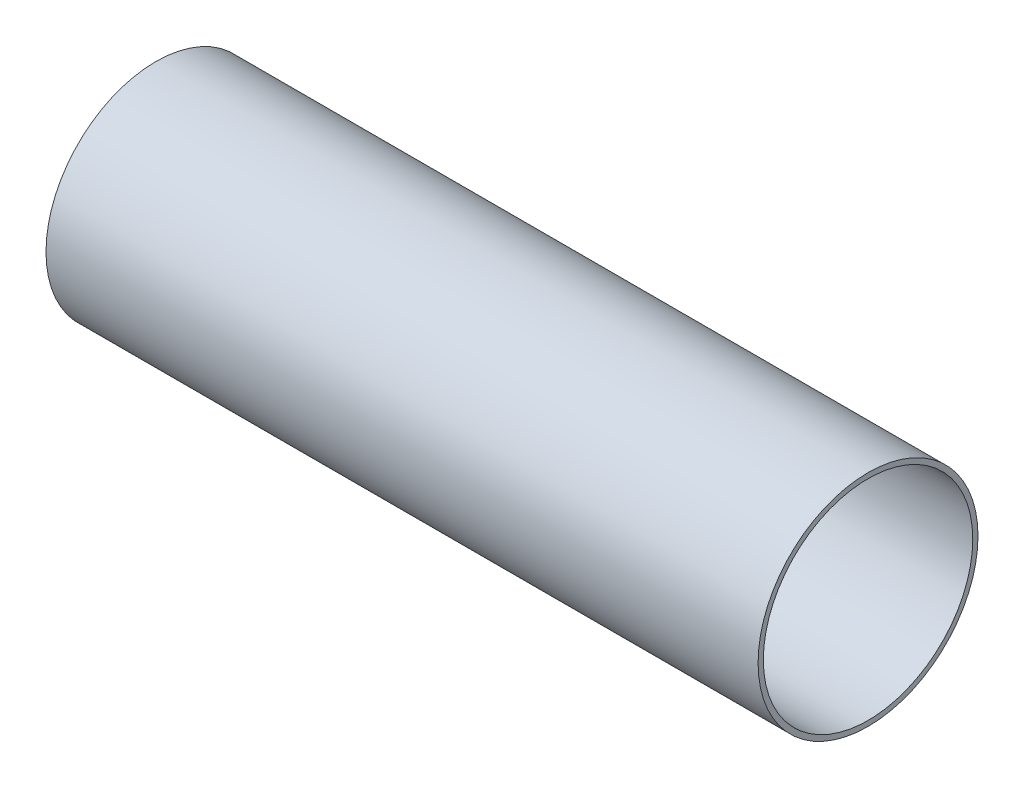
SolidWorks part; units mm, degrees
material "CMR DEFAULT - CHANGE MATERIAL"
ref_plane "XY PLANE - TOP" through (0, 0, 0) normal (0, 0, 1) x (1, 0, 0)
ref_plane "XZ PLANE - SIDE" through (0, 0, 0) normal (0, 1, 0) x (1, 0, 0)
ref_plane "YZ PLANE - FRONT" through (0, 0, 0) normal (1, 0, 0) x (0, 0, -1)
sketch "Sketch1" plane through (0, 0, 0) normal (1, 0, 0) x (0, 0, -1)
  circle A0 centre (0, 0) radius 63.5
  circle A1 centre (0, 0) radius 66.675
  dimension "D1" = 127
  dimension "D2" = 3.175
extrude "Boss-Extrude1" add sketch "Sketch1" along normal blind 431.8
